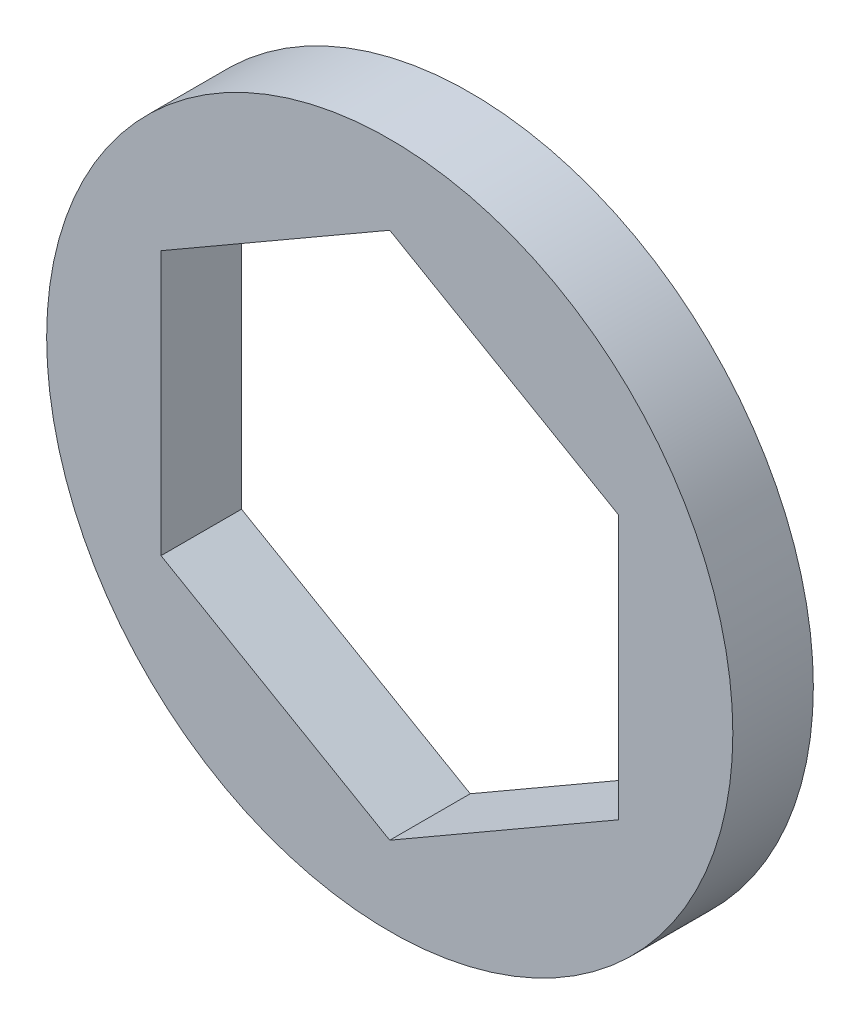
SolidWorks part; units mm, degrees
ref_plane "Front Plane" through (0, 0, 0) normal (0, 0, 1) x (1, 0, 0)
ref_plane "Top Plane" through (0, 0, 0) normal (0, 1, 0) x (1, 0, 0)
ref_plane "Right Plane" through (0, 0, 0) normal (1, 0, 0) x (0, 0, -1)
sketch "Sketch1" plane through (0, 0, 0) normal (0, 0, 1) x (1, 0, 0)
  line L1 (0, 7.3323) -> (-6.35, 3.6662)
  line L2 (-6.35, 3.6662) -> (-6.35, -3.6662)
  line L3 (-6.35, -3.6662) -> (0, -7.3323)
  line L4 (0, -7.3323) -> (6.35, -3.6662)
  line L5 (6.35, -3.6662) -> (6.35, 3.6662)
  line L6 (6.35, 3.6662) -> (0, 7.3323)
  circle A0 centre (0, 0) radius 6.35 construction
  circle A1 centre (0, 0) radius 9.525
  dimension "D1" = 12.7
  dimension "D2" = 19.05
extrude "Boss-Extrude1" add sketch "Sketch1" along normal blind 2.2352
